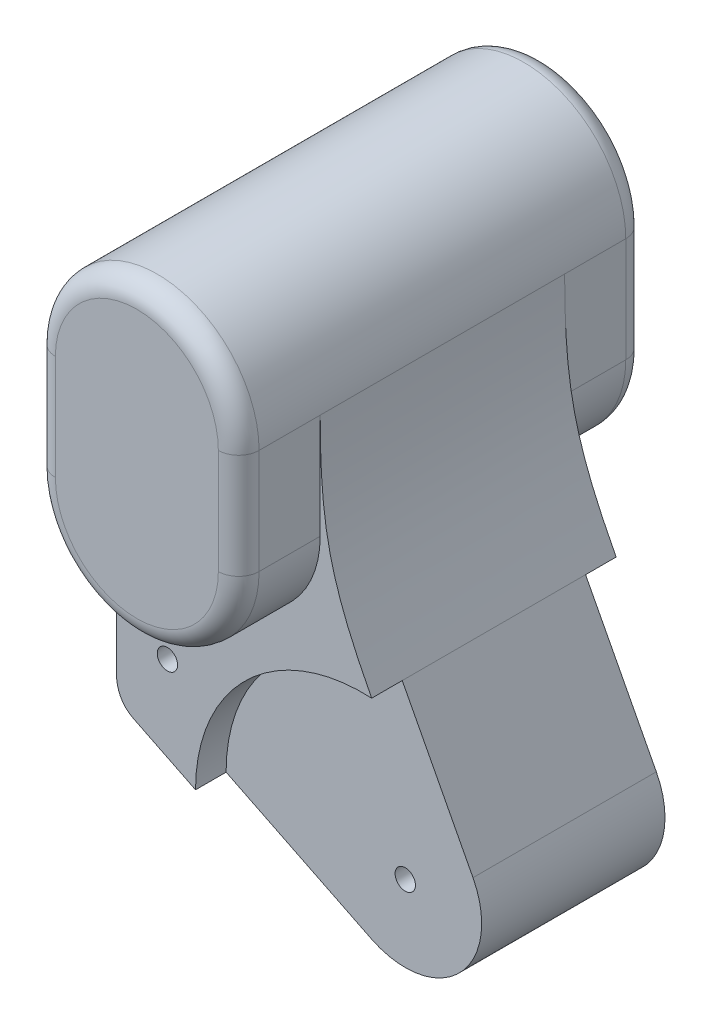
SolidWorks part; units mm, degrees
ref_plane "Front Plane" through (0, 0, 0) normal (0, 0, 1) x (1, 0, 0)
ref_plane "Top Plane" through (0, 0, 0) normal (0, 1, 0) x (1, 0, 0)
ref_plane "Right Plane" through (0, 0, 0) normal (1, 0, 0) x (0, 0, -1)
sketch "SketchDistalInternal" plane through (0, 0, 0) normal (0, 0, 1) x (1, 0, 0)
  line L0 (0.8395, -1.4871) -> (11.0161, -6.5129)
  line L1 (16, -1.4134) -> (12.5271, 5.2306)
  line L3 (2.5, 1.8752) -> (0.8395, -1.4871) construction
  line L4 (2.5, 1.8752) -> (12.6766, -3.1506) construction
  line L5 (0, 16) -> (0, 0)
  circle A0 centre (2.5, 1.8752) radius 0.5
  circle A1 centre (12.6766, -3.1506) radius 0.5
  arc A2 (0, 16) -> (10, 16) centre (5, 16) cw
  arc A3 (11.0161, -6.5129) -> (16, -1.4134) centre (12.6766, -3.1506) ccw
  spline S0 degree 3 poles (0, 0) (0, -0.5402) (0.1916, -1.1671) (0.8395, -1.4871) knots 0 0 0 0 1 1 1 1
  spline S1 degree 3 poles (10, 16) (10, 11.2957) (10.4737, 9.1589) (12.5271, 5.2306) knots 0 0 0 0 1 1 1 1
  point P1 (15.3585, -5.7716)
  point P6 (5.9278, -4)
  point P7 (9.5, 18.1794)
  point P12 (9.5, 18.1794)
  point P13 (9.9575, 15.3494)
  point P18 (0, 0)
  dimension "D3" = 3.75
  dimension "D5" = 116.283
  dimension "D6" = 3.75
  dimension "D7" = 5
  dimension "D8" = 1
  dimension "D9" = 20
  dimension "D11" = 16
  dimension "D4" = 2.5
  dimension "D1" = 16
  dimension "D2" = 11.35
extrude "BossExtrudeDistalInternal" add sketch "SketchDistalInternal" along normal blind 12
sketch "SketchCutBarL" plane through (0, 0, 12) normal (0, 0, 1) x (1, 0, 0)
  line L0 (3.8806, -2.989) -> (11.0161, -6.5129)
  line L1 (0.8395, -1.4871) -> (11.0161, -6.5129) construction
  line L2 (16, -1.4134) -> (12.5271, 5.2306)
  arc A0 (11.0161, -6.5129) -> (16, -1.4134) centre (12.6766, -3.1506) ccw
  arc A1 (12.5271, 5.2306) -> (3.8806, -2.989) centre (12.1032, -2.981) ccw
  point P11 (3.8645, -2.981)
extrude "CutExtrudeDistalBarL" cut sketch "SketchCutBarL" against normal blind 1.5
sketch "SketchCutBarR" plane through (0, 0, 0) normal (0, 0, 1) x (1, 0, 0)
  line L0 (3.8806, -2.989) -> (11.0161, -6.5129)
  line L2 (16, -1.4134) -> (12.5271, 5.2306)
  arc A0 (11.0161, -6.5129) -> (16, -1.4134) centre (12.6766, -3.1506) ccw
  arc A1 (12.5271, 5.2306) -> (3.8806, -2.989) centre (12.1032, -2.981) ccw
  point P11 (3.8645, -2.981)
extrude "CutExtrudeDistalBarR" cut sketch "SketchCutBarR" along normal blind 1.5
sketch "SketchDistalExternal" plane through (0, 0, 12) normal (0, 0, 1) x (1, 0, 0)
  line L0 (0, 16) -> (0, 10.8509)
  line L1 (0, 16) -> (0, 0) construction
  line L2 (10, 10.8509) -> (10, 16)
  arc A0 (0, 16) -> (10, 16) centre (5, 16) cw
  arc A1 (0, 10.8509) -> (10, 10.8509) centre (5, 10.8509) ccw
extrude "BossExtrudeExternal" add sketch "SketchDistalExternal" against normal blind 20 from offset 4
fillet "FilletDistalExternal" radius 1 8 edges at (10, 13.4255, -4) (5, 21, -4) (0, 13.4255, -4) (5, 5.8509, -4) (5, 5.8509, 16) (0, 13.4255, 16) (5, 21, 16) (10, 13.4255, 16)
